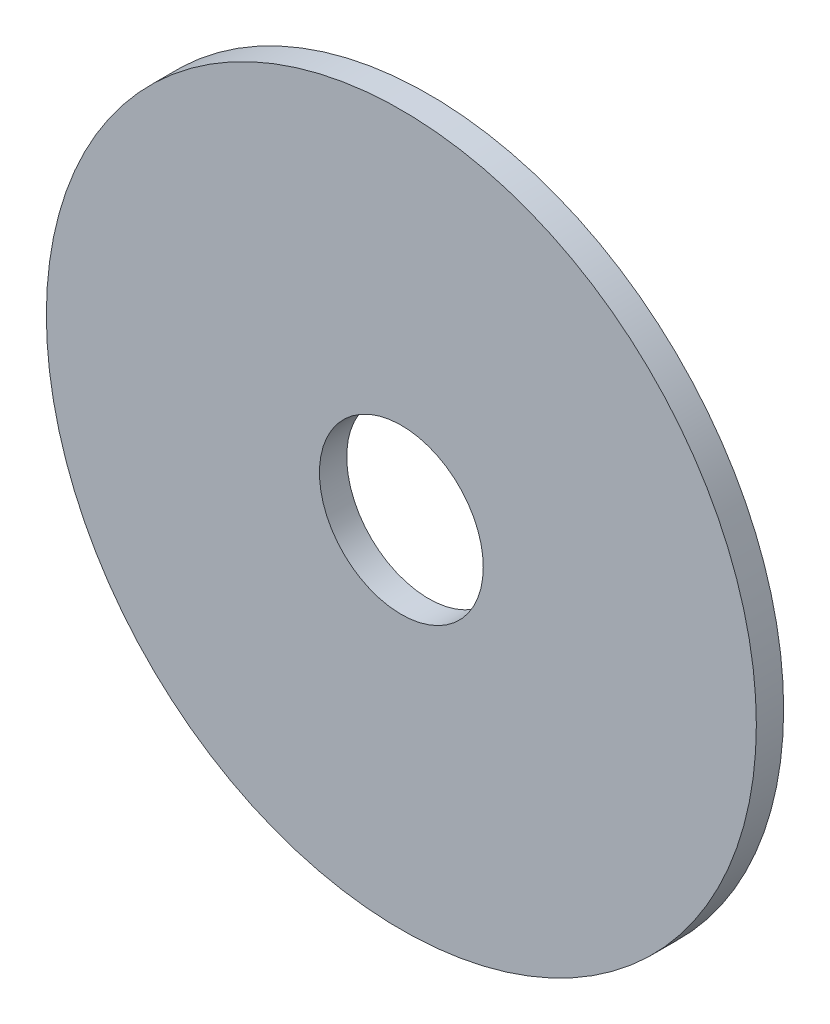
SolidWorks part; units mm, degrees
material "Thornel Mat VMA"
ref_plane "前视基准面" through (0, 0, 0) normal (0, 0, 1) x (1, 0, 0)
ref_plane "上视基准面" through (0, 0, 0) normal (0, 1, 0) x (1, 0, 0)
ref_plane "右视基准面" through (0, 0, 0) normal (1, 0, 0) x (0, 0, -1)
sketch "草图1" plane through (0, 0, 0) normal (0, 0, 1) x (1, 0, 0)
  circle A0 centre (0, 0) radius 13
  dimension "D1" = 26
extrude "凸台-拉伸1" add sketch "草图1" along normal blind 1
sketch "草图2" plane through (0, 0, 1) normal (0, 0, 1) x (1, 0, 0)
  circle A0 centre (0, 0) radius 3
  dimension "D1" = 6
extrude "切除-拉伸1" cut sketch "草图2" against normal blind 1
